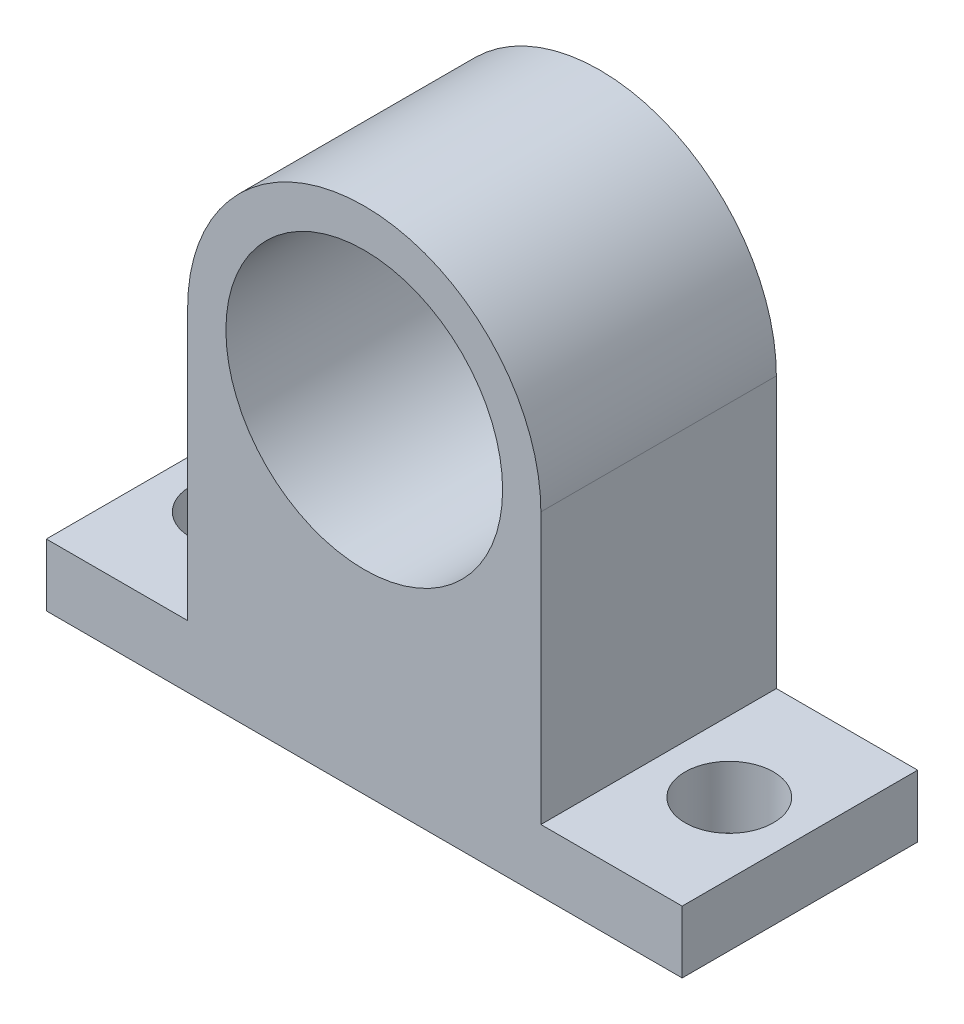
SolidWorks part; units mm, degrees
ref_plane "Front Plane" through (0, 0, 0) normal (0, 0, 1) x (1, 0, 0)
ref_plane "Top Plane" through (0, 0, 0) normal (0, 1, 0) x (1, 0, 0)
ref_plane "Right Plane" through (0, 0, 0) normal (1, 0, 0) x (0, 0, -1)
sketch "Sketch1" plane through (0, 0, 0) normal (0, 0, 1) x (1, 0, 0)
  line L0 (-30, 0) -> (-30, -45.9916)
  line L1 (30, 0) -> (30, -45.9916)
  line L2 (-30, -45.9916) -> (-54, -45.9916)
  line L3 (-54, -45.9916) -> (-54, -56.5687)
  line L4 (-54, -56.5687) -> (54, -56.5687)
  line L5 (54, -56.5687) -> (54, -45.9916)
  line L6 (54, -45.9916) -> (30, -45.9916)
  arc A0 (30, 0) -> (-30, 0) centre (0, 0) ccw
  circle A1 centre (0, 0) radius 23.5
  dimension "D1" = 47
  dimension "D2" = 60
  dimension "D3" = 24
  dimension "D4" = 24
  dimension "D5" = 45.9916
extrude "Boss-Extrude1" add sketch "Sketch1" along normal blind 40
sketch "Sketch2" plane through (0, -45.9916, 0) normal (0, 1, 0) x (1, 0, 0)
  line L0 (42, 0) -> (42, -40) construction
  line L1 (54, 0) -> (30, 0) construction
  line L2 (54, -40) -> (30, -40) construction
  line L3 (0, 0) -> (0, -40) construction
  line L4 (30, 0) -> (-30, 0) construction
  line L5 (-30, -40) -> (30, -40) construction
  circle A0 centre (42, -20) radius 7.5
  circle A1 centre (-42, -20) radius 7.5
  dimension "D1" = 15
extrude "Cut-Extrude1" cut sketch "Sketch2" against normal through all both and the other way through all
